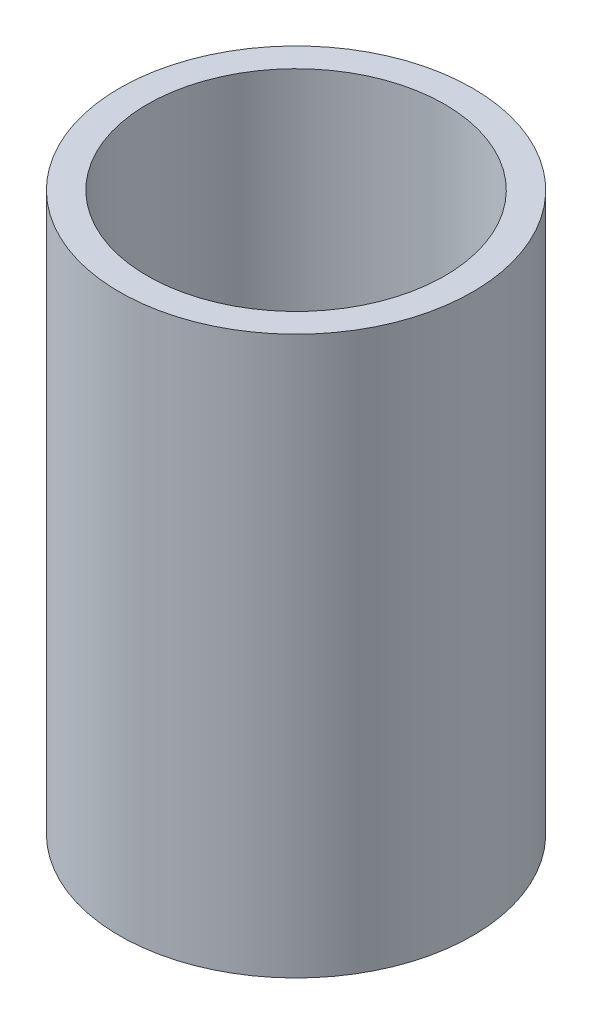
SolidWorks part; units mm, degrees
ref_plane "Front Plane" through (0, 0, 0) normal (0, 0, 1) x (1, 0, 0)
ref_plane "Top Plane" through (0, 0, 0) normal (0, 1, 0) x (1, 0, 0)
ref_plane "Right Plane" through (0, 0, 0) normal (1, 0, 0) x (0, 0, -1)
sketch "Sketch1" plane through (0, 0, 0) normal (0, 1, 0) x (1, 0, 0)
  circle A0 centre (0, 0) radius 24.13
  dimension "D1" = 48.26
extrude "Boss-Extrude1" add sketch "Sketch1" along normal blind 76.2
sketch "Sketch2" plane through (0, 0, 0) normal (0, -1, 0) x (-1, 0, 0)
  circle A0 centre (0, 0) radius 20.32
extrude "Cut-Extrude1" cut sketch "Sketch2" against normal through all contours A0
